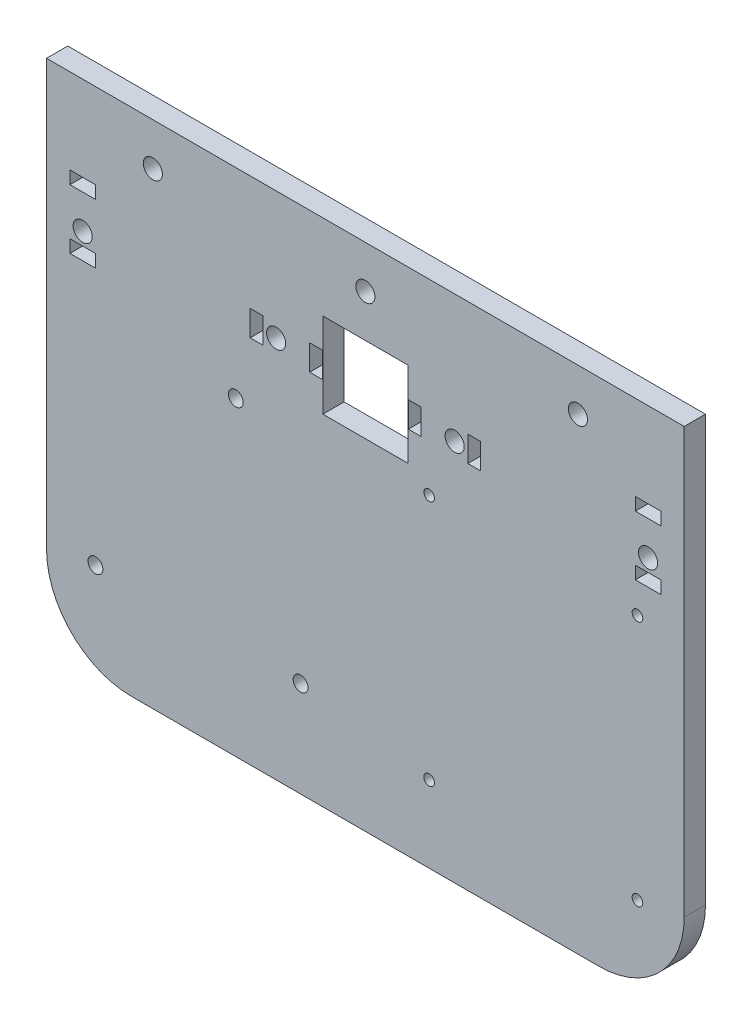
SolidWorks part; units mm, degrees
ref_plane "Plan de face" through (0, 0, 0) normal (0, 0, 1) x (1, 0, 0)
ref_plane "Plan de dessus" through (0, 0, 0) normal (0, 1, 0) x (1, 0, 0)
ref_plane "Plan de droite" through (0, 0, 0) normal (1, 0, 0) x (0, 0, -1)
sketch "Esquisse1" plane through (0, 0, 0) normal (0, 0, 1) x (1, 0, 0)
  line L0 (90, -44) -> (139, -44) construction
  line L1 (0, 0) -> (150, 0)
  line L2 (0, 0) -> (0, -100)
  line L3 (20, -120) -> (130, -120)
  line L4 (150, 0) -> (150, -100)
  line L5 (65, -20) -> (85, -20)
  line L6 (65, -20) -> (65, -40)
  line L7 (65, -40) -> (85, -40)
  line L8 (85, -20) -> (85, -40)
  line L9 (139, -44) -> (139, -102) construction
  line L10 (139, -102) -> (90, -102) construction
  line L11 (90, -102) -> (90, -44) construction
  line L12 (8.5, -31) -> (141.5, -31) construction
  line L13 (25, -10) -> (125, -10) construction
  line L14 (99, -28) -> (93, -32) construction
  line L15 (57, -32) -> (51, -28) construction
  line L16 (11.5, -97.5) -> (59.76, -97.5) construction
  line L17 (5.5, -34) -> (11.5, -34)
  line L18 (5.5, -34) -> (5.5, -37)
  line L19 (5.5, -37) -> (11.5, -37)
  line L20 (11.5, -34) -> (11.5, -37)
  line L21 (5.5, -20) -> (11.5, -20)
  line L22 (5.5, -20) -> (5.5, -23)
  line L23 (5.5, -23) -> (11.5, -23)
  line L24 (11.5, -20) -> (11.5, -23)
  line L25 (138.5, -34) -> (144.5, -34)
  line L26 (138.5, -34) -> (138.5, -37)
  line L27 (138.5, -37) -> (144.5, -37)
  line L28 (144.5, -34) -> (144.5, -37)
  line L29 (138.5, -20) -> (144.5, -20)
  line L30 (138.5, -20) -> (138.5, -23)
  line L31 (138.5, -23) -> (144.5, -23)
  line L32 (144.5, -20) -> (144.5, -23)
  line L33 (99.1, -27) -> (102.1, -27)
  line L34 (99.1, -27) -> (99.1, -33)
  line L35 (99.1, -33) -> (102.1, -33)
  line L36 (102.1, -27) -> (102.1, -33)
  line L37 (85.1, -27) -> (88.1, -27)
  line L38 (85.1, -27) -> (85.1, -33)
  line L39 (85.1, -33) -> (88.1, -33)
  line L40 (88.1, -27) -> (88.1, -33)
  line L41 (47.9, -27) -> (50.9, -27)
  line L42 (47.9, -27) -> (47.9, -33)
  line L43 (47.9, -33) -> (50.9, -33)
  line L44 (50.9, -27) -> (50.9, -33)
  line L45 (61.9, -27) -> (64.9, -27)
  line L46 (61.9, -27) -> (61.9, -33)
  line L47 (61.9, -33) -> (64.9, -33)
  line L48 (64.9, -27) -> (64.9, -33)
  line L49 (11.5, -97.5) -> (11.5, -47) construction
  line L50 (11.5, -47) -> (44.52, -47) construction
  circle A0 centre (90, -44) radius 1.25
  circle A1 centre (139, -44) radius 1.25
  circle A2 centre (139, -102) radius 1.25
  circle A3 centre (90, -102) radius 1.25
  circle A4 centre (8.5, -31) radius 2.25
  circle A5 centre (141.5, -31) radius 2.25
  circle A6 centre (25, -10) radius 2.25
  circle A7 centre (125, -10) radius 2.25
  circle A8 centre (96, -30) radius 2.25
  circle A9 centre (54, -30) radius 2.25
  circle A10 centre (75, -10) radius 2.25
  arc A11 (0, -100) -> (20, -120) centre (20, -100) ccw
  arc A12 (130, -120) -> (150, -100) centre (130, -100) ccw
  circle A13 centre (11.5, -97.5) radius 1.75
  circle A14 centre (59.76, -97.5) radius 1.75
  circle A16 centre (44.52, -47) radius 1.75
  point P25 (75, -10)
  point P42 (0, -120)
  point P77 (49.4, -33)
  dimension "D6" = 2.5
  dimension "D11" = 4.5
  dimension "D19" = 20
  dimension "D40" = 3.5
  dimension "D1" = 150
  dimension "D2" = 120
  dimension "D3" = 20
  dimension "D4" = 20
  dimension "D5" = 65
  dimension "D7" = 58
  dimension "D8" = 49
  dimension "D9" = 11
  dimension "D10" = 18
  dimension "D12" = 8.5
  dimension "D13" = 8.5
  dimension "D14" = 31
  dimension "D15" = 31
  dimension "D16" = 10
  dimension "D17" = 100
  dimension "D18" = 75
  dimension "D20" = 6
  dimension "D21" = 3
  dimension "D22" = 5.5
  dimension "D23" = 5.5
  dimension "D24" = 5.5
  dimension "D25" = 5.5
  dimension "D26" = 17
  dimension "D27" = 17
  dimension "D28" = 37
  dimension "D29" = 37
  dimension "D30" = 6
  dimension "D31" = 3
  dimension "D32" = 17
  dimension "D33" = 17
  dimension "D34" = 33
  dimension "D35" = 33
  dimension "D36" = 33
  dimension "D37" = 33
  dimension "D38" = 47.9
  dimension "D39" = 47.9
  dimension "D41" = 48.26
  dimension "D42" = 33.02
  dimension "D43" = 50.5
  dimension "D44" = 45
extrude "Boss.-Extru.1" add sketch "Esquisse1" along normal blind 5
